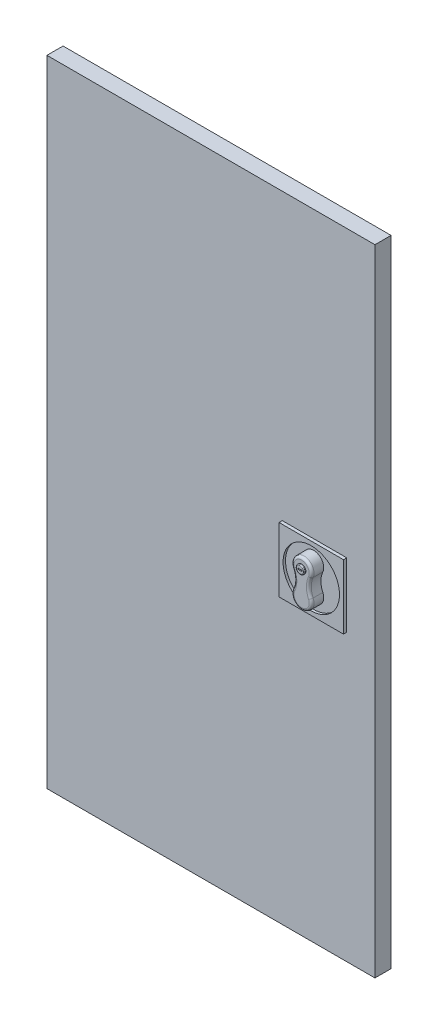
SolidWorks part; units mm, degrees
ref_plane "Front" through (0, 0, 0) normal (0, 0, 1) x (1, 0, 0)
ref_plane "Top" through (0, 0, 0) normal (0, 1, 0) x (1, 0, 0)
ref_plane "Right" through (0, 0, 0) normal (1, 0, 0) x (0, 0, -1)
sketch "Sketch1" plane through (0, 0, 0) normal (0, 0, 1) x (1, 0, 0)
  line L1 (-203.5, -394) -> (203.5, -394)
  line L2 (-203.5, -394) -> (-203.5, 394)
  line L3 (-203.5, 394) -> (203.5, 394)
  line L4 (203.5, -394) -> (203.5, 394)
  line L5 (-203.5, -394) -> (203.5, 394) construction
  line L6 (-203.5, 394) -> (203.5, -394) construction
  point P0 (0, 0)
  dimension "D1" = 407
  dimension "D2" = 788
extrude "Boss-Extrude1" add sketch "Sketch1" along normal mid plane 20
shell "Shell1" thickness 1.5
sketch "Sketch2" plane through (0, 0, 10) normal (0, 0, 1) x (1, 0, 0)
  line L1 (88.5, -40) -> (168.5, -40)
  line L2 (88.5, -40) -> (88.5, 40)
  line L3 (88.5, 40) -> (168.5, 40)
  line L4 (168.5, -40) -> (168.5, 40)
  line L5 (88.5, -40) -> (168.5, 40) construction
  line L6 (88.5, 40) -> (168.5, -40) construction
  line L7 (203.5, -394) -> (203.5, 394) construction
  point P0 (128.5, 0)
  point P5 (158.6898, 0)
  point P6 (113.7494, 0)
  point P9 (0, 0)
  dimension "D1" = 80
  dimension "D2" = 80
  dimension "D3" = 35
extrude "Boss-Extrude2" add sketch "Sketch2" along normal blind 4
sketch "Sketch3" plane through (0, 0, 14) normal (0, 0, 1) x (1, 0, 0)
  circle A0 centre (128.5, 0) radius 35
  point P2 (0, 0)
  dimension "D1" = 70
extrude "Cut-Extrude1" cut sketch "Sketch3" against normal blind 3
sketch "Sketch4" plane through (0, 0, 11) normal (0, 0, 1) x (1, 0, 0)
  line L0 (128.5, 16.1227) -> (128.5, -16.1227) construction
  arc A0 (139.828, 11.0188) -> (117.172, 11.0188) centre (128.5, 16.1227) ccw
  arc A1 (117.172, -11.0188) -> (139.828, -11.0188) centre (128.5, -16.1227) ccw
  arc A2 (139.828, 11.0188) -> (139.828, -11.0188) centre (164.2842, 0) ccw
  arc A3 (117.172, 11.0188) -> (117.172, -11.0188) centre (92.7158, 0) cw
  point P1 (139.828, 11.0188)
extrude "Boss-Extrude3" add sketch "Sketch4" along normal blind 15
sketch "Sketch5" plane through (0, 0, 26) normal (0, 0, 1) x (1, 0, 0)
  circle A0 centre (128.5, 16.1227) radius 5.2842
extrude "Boss-Extrude4" add sketch "Sketch5" along normal blind 2
fillet "Fillet1" radius 3 4 edges at (137.4604, 0, 26) (128.5, -28.5475, 26) (119.5396, 0, 26) (128.5, 28.5475, 26)
fillet "Fillet2" radius 1 1 edges at (133.7842, 16.1227, 28)
sketch "Sketch6" plane through (0, 0, 28) normal (0, 0, 1) x (1, 0, 0)
  line L1 (125.8019, 15.4928) -> (131.1981, 15.4928)
  line L2 (125.8019, 15.4928) -> (125.8019, 16.7527)
  line L3 (125.8019, 16.7527) -> (131.1981, 16.7527)
  line L4 (131.1981, 15.4928) -> (131.1981, 16.7527)
  line L5 (125.8019, 15.4928) -> (131.1981, 16.7527) construction
  line L6 (125.8019, 16.7527) -> (131.1981, 15.4928) construction
  point P0 (128.5, 16.1227)
extrude "Cut-Extrude2" cut sketch "Sketch6" against normal blind 5
sketch "Sketch7" plane through (0, 394, 0) normal (0, 1, 0) x (1, 0, 0)
  line L0 (203.5, -10) -> (-203.5, -10) construction
  line L1 (-203.5, -10) -> (-203.5, 10) construction
  circle A0 centre (-193.5, -3) radius 2
  circle A1 centre (-193.5, -3) radius 6
  dimension "D1" = 12
  dimension "D2" = 4
  dimension "D3" = 13
  dimension "D4" = 16
extrude "Boss-Extrude5" add sketch "Sketch7" against normal blind 12.5 from offset 71.5 offset against normal yes
ref_plane "Plane1" through (0, 292, 0) normal (0, -1, 0) x (-1, 0, 0)
mirror "Mirror1" about plane through (0, 292, 0) normal (0, -1, 0) of "Boss-Extrude5"
mirror "Mirror2" about plane through (0, 0, 0) normal (0, 1, 0) of "Boss-Extrude5", "Mirror1"
